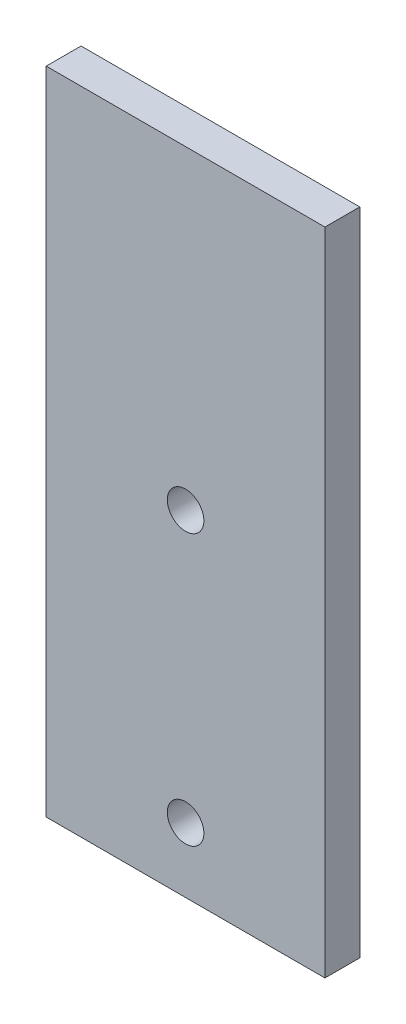
SolidWorks part; units mm, degrees
ref_plane "Front Plane" through (0, 0, 0) normal (0, 0, 1) x (1, 0, 0)
ref_plane "Top Plane" through (0, 0, 0) normal (0, 1, 0) x (1, 0, 0)
ref_plane "Right Plane" through (0, 0, 0) normal (1, 0, 0) x (0, 0, -1)
sketch "Sketch1" plane through (0, 0, 0) normal (0, 0, 1) x (1, 0, 0)
  line L0 (19.05, 45.85) -> (19.05, 8.85) construction
  line L1 (0, 0) -> (38.1, 0)
  line L2 (0, 0) -> (0, 88.9)
  line L3 (0, 88.9) -> (38.1, 88.9)
  line L4 (38.1, 0) -> (38.1, 88.9)
  circle A2 centre (19.05, 8.85) radius 2.5
  circle A3 centre (19.05, 45.85) radius 2.5
  point P5 (19.05, 0)
  point P7 (18.4093, 15.2)
  point P13 (18.7191, 7.5285)
  point P14 (19.4936, 7.2187)
  dimension "D3" = 5
  dimension "D4" = 6.35
  dimension "D5" = 5
  dimension "D1" = 38.1
  dimension "D2" = 88.9
  dimension "D7" = 37
extrude "Boss-Extrude1" add sketch "Sketch1" along normal blind 4.7625
